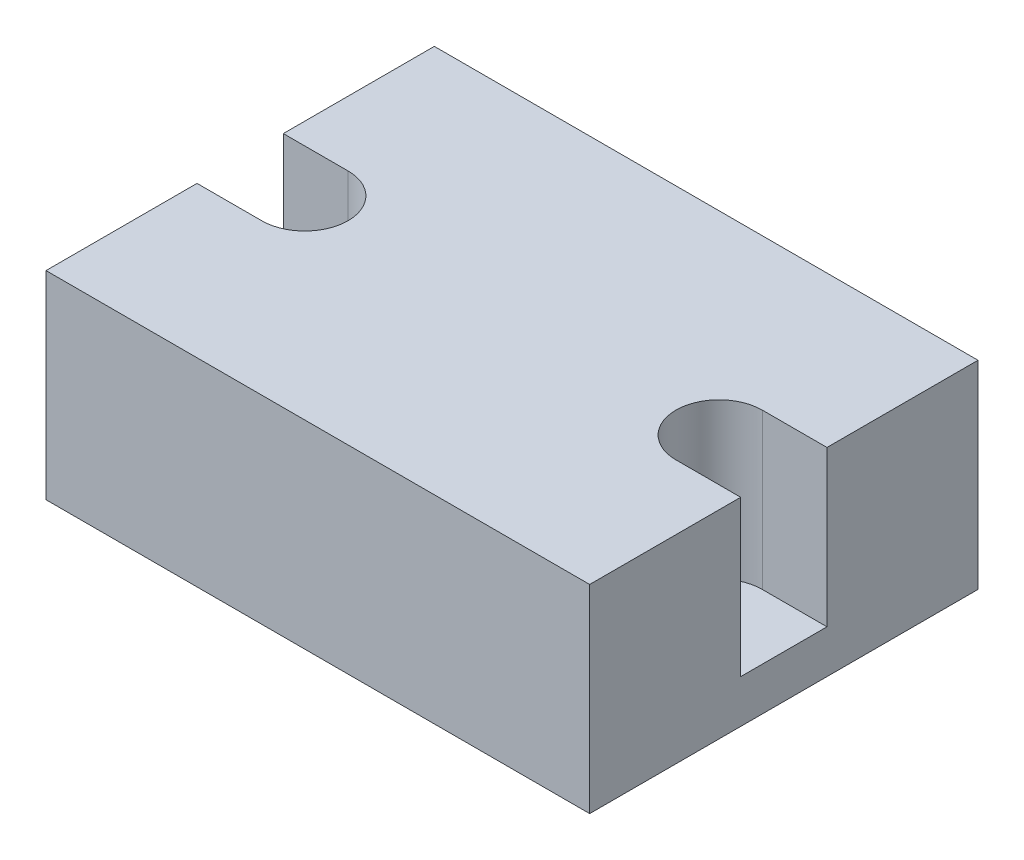
SolidWorks part; units mm, degrees
ref_plane "Front Plane" through (0, 0, 0) normal (0, 0, 1) x (1, 0, 0)
ref_plane "Top Plane" through (0, 0, 0) normal (0, 1, 0) x (1, 0, 0)
ref_plane "Right Plane" through (0, 0, 0) normal (1, 0, 0) x (0, 0, -1)
sketch "Sketch1" plane through (0, 0, 0) normal (0, 1, 0) x (1, 0, 0)
  line L1 (-31.5, -22.5) -> (31.5, -22.5)
  line L2 (-31.5, -22.5) -> (-31.5, 22.5)
  line L3 (-31.5, 22.5) -> (31.5, 22.5)
  line L4 (31.5, -22.5) -> (31.5, 22.5)
  line L5 (-31.5, -22.5) -> (31.5, 22.5) construction
  line L6 (-31.5, 22.5) -> (31.5, -22.5) construction
  point P0 (0, 0)
  dimension "D1" = 45
  dimension "D2" = 63
extrude "Boss-Extrude1" add sketch "Sketch1" along normal blind 23
sketch "Sketch2" plane through (0, 23, 0) normal (0, 1, 0) x (1, 0, 0)
  line L0 (24, 0) -> (38.957, 0) construction
  line L1 (24, 5) -> (38.957, 5)
  line L2 (24, -5) -> (38.957, -5)
  line L3 (0, 0) -> (0, 44.5269) construction
  line L4 (-24, 0) -> (-38.957, 0) construction
  line L5 (-24, 5) -> (-38.957, 5)
  line L6 (-24, -5) -> (-38.957, -5)
  arc A0 (24, 5) -> (24, -5) centre (24, 0) ccw
  arc A1 (38.957, -5) -> (38.957, 5) centre (38.957, 0) ccw
  arc A2 (-24, 5) -> (-24, -5) centre (-24, 0) cw
  arc A3 (-38.957, -5) -> (-38.957, 5) centre (-38.957, 0) cw
  point P3 (31.4785, 0)
  point P12 (-31.4785, 0)
  dimension "D2" = 38
  dimension "D1" = 10
extrude "Cut-Extrude1" cut sketch "Sketch2" against normal offset from surface (18 mm away) 5 up to face at (0, 0, 0)
